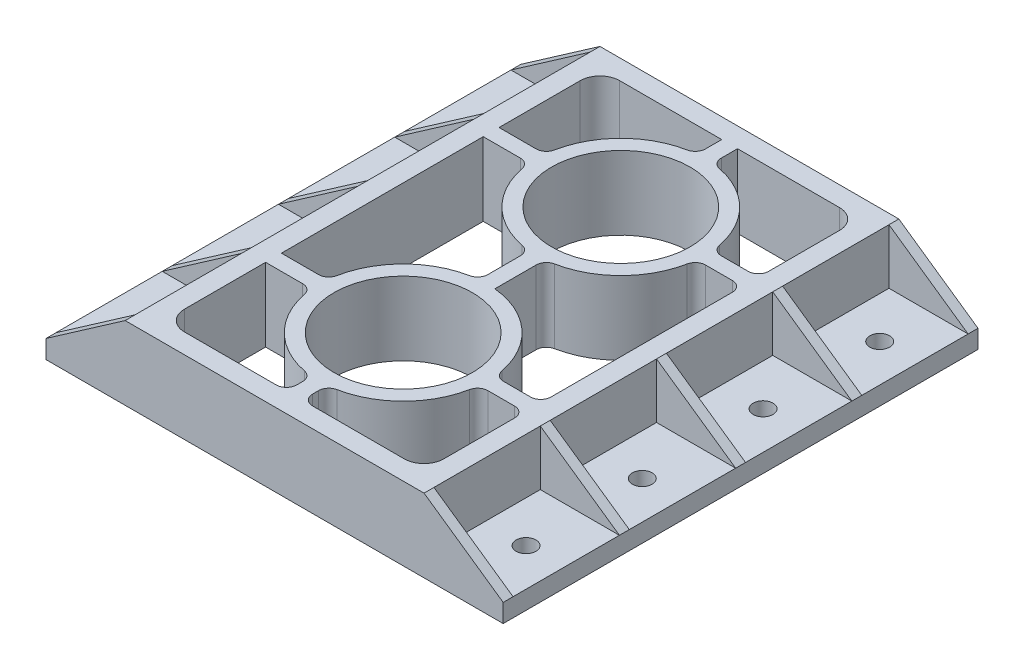
SolidWorks part; units mm, degrees
ref_plane "Front Plane" through (0, 0, 0) normal (0, 0, 1) x (1, 0, 0)
ref_plane "Top Plane" through (0, 0, 0) normal (0, 1, 0) x (1, 0, 0)
ref_plane "Right Plane" through (0, 0, 0) normal (1, 0, 0) x (0, 0, -1)
sketch "Sketch1" plane through (0, 0, 0) normal (0, 0, 1) x (1, 0, 0)
  line L0 (39.1322, 0) -> (112.5008, 0)
  line L1 (112.5008, 0) -> (112.5008, 5.8909)
  line L2 (112.5008, 5.8909) -> (87.1008, 5.8909)
  line L3 (87.1008, 5.8909) -> (87.1008, 23.5635)
  line L4 (87.1008, 23.5635) -> (39.1322, 23.5635)
  line L5 (39.1322, 23.5635) -> (39.1322, 0)
  dimension "D1" = 25.4
extrude "Extrude1" add sketch "Sketch1" against normal blind 152.4
mirror "Mirror1" about plane through (39.1322, 23.5635, -152.4) normal (-1, 0, 0) of "Extrude1"
ref_plane "Plane1" through (39.4584, 56.7117, 0) normal (-0.5711, -0.8209, 0) x (0.8209, -0.5711, 0)
ref_plane "Plane4" through (0, 0, 0) normal (0, 0, 1) x (1, 0, 0)
sketch "Sketch6" plane through (0, 0, 0) normal (0, 0, 1) x (1, 0, 0)
  line L0 (87.1008, 23.5635) -> (112.5008, 5.8909)
  line L1 (112.5008, 5.8909) -> (87.1008, 5.8909)
  line L2 (87.1008, 5.8909) -> (87.1008, 23.5635)
extrude "Extrude2" add sketch "Sketch6" against normal blind 3.175
ref_plane "Plane5" through (0, 0, -152.4) normal (0, 0, -1) x (-1, 0, 0)
ref_plane "Plane6" through (0, 5.8909, 0) normal (0, 1, 0) x (-1, 0, 0)
sketch "Sketch8" plane through (0, 5.8909, 0) normal (0, 1, 0) x (-1, 0, 0)
  circle A0 centre (-100.3959, -19.4469) radius 3.175
  circle A1 centre (-100.3959, -56.7531) radius 3.175
  circle A2 centre (-100.3959, -95.519) radius 3.175
  circle A3 centre (-100.3959, -132.9531) radius 3.175
extrude "Extrude4" cut sketch "Sketch8" against normal through all
pattern_linear "LPattern1" count 5 spacing 37.3062 along (0, 0, -1) of "Extrude2"
ref_plane "Plane8" through (39.1322, 0, 0) normal (1, 0, 0) x (0, 0, -1)
mirror "Mirror5" about plane through (39.1322, 0, 0) normal (1, 0, 0) of "LPattern1", "Extrude4", "Extrude2"
ref_plane "Plane9" through (0, 23.5635, 0) normal (0, 1, 0) x (-1, 0, 0)
sketch "Sketch11" plane through (0, 23.5635, 0) normal (0, 1, 0) x (-1, 0, 0)
  line L51 (-80.7508, -139.7) -> (-80.7508, -12.7)
  line L52 (2.4863, -139.7) -> (2.4863, -12.7)
  line L80 (2.4863, -6.35) -> (-80.7508, -6.35)
  line L81 (-80.7508, -6.35) -> (-80.7508, -37.3062)
  line L82 (-80.7508, -37.3062) -> (-80.7508, -40.4813)
  line L83 (-80.7508, -40.4813) -> (-80.7508, -74.6125)
  line L84 (-80.7508, -74.6125) -> (-80.7508, -77.7875)
  line L85 (-80.7508, -77.7875) -> (-80.7508, -111.9188)
  line L86 (-80.7508, -111.9188) -> (-80.7508, -115.0938)
  line L87 (-80.7508, -115.0938) -> (-80.7508, -146.05)
  line L88 (-80.7508, -146.05) -> (2.4863, -146.05)
  line L89 (2.4863, -146.05) -> (2.4863, -115.0938)
  line L90 (2.4863, -115.0938) -> (2.4863, -111.9188)
  line L91 (2.4863, -111.9188) -> (2.4863, -77.7875)
  line L92 (2.4863, -77.7875) -> (2.4863, -74.6125)
  line L93 (2.4863, -74.6125) -> (2.4863, -40.4813)
  line L94 (2.4863, -40.4813) -> (2.4863, -37.3063)
  line L95 (2.4863, -37.3063) -> (2.4863, -6.35)
  line L96 (-3.8637, -6.35) -> (-74.4008, -6.35)
  line L104 (-74.4008, -146.05) -> (-3.8637, -146.05)
  arc A0 (-74.4008, -6.35) -> (-80.7508, -12.7) centre (-74.4008, -12.7) ccw
  arc A1 (-3.8637, -6.35) -> (2.4863, -12.7) centre (-3.8637, -12.7) cw
  arc A2 (-3.8637, -146.05) -> (2.4863, -139.7) centre (-3.8637, -139.7) ccw
  arc A3 (-80.7508, -139.7) -> (-74.4008, -146.05) centre (-74.4008, -139.7) ccw
  dimension "D2" = 6.35
extrude "Extrude5" cut sketch "Sketch11" against normal blind 25.4
sketch "Sketch12" plane through (0, 23.5635, 0) normal (0, 1, 0) x (-1, 0, 0)
  line L3 (-80.7508, -76.2) -> (2.4863, -76.2) construction
  line L4 (-80.7508, -12.7) -> (-80.7508, -139.7) construction
  line L5 (2.4863, -139.7) -> (2.4863, -12.7) construction
  circle A0 centre (-39.1322, -41.275) radius 22.225
  circle A1 centre (-39.1322, -111.125) radius 22.225
extrude "Extrude-Thin2" add sketch "Sketch12" against normal up to vertex thin
sketch "Sketch13" plane through (0, 23.5635, 0) normal (0, 1, 0) x (-1, 0, 0)
  line L0 (-80.7508, -38.735) -> (-80.7508, -43.815)
  line L1 (-41.6722, -2.8575) -> (-36.5922, -2.8575)
  line L2 (-80.7508, -43.815) -> (-62.9708, -43.815)
  line L3 (-41.6722, -66.3575) -> (-36.5922, -66.3575)
  line L4 (-62.9708, -38.735) -> (-62.9708, -43.815)
  line L5 (-41.6722, -86.6775) -> (-36.5922, -86.6775)
  line L6 (-14.6847, -38.735) -> (-14.6847, -43.815)
  line L7 (4.3653, -38.735) -> (4.3653, -43.815)
  line L8 (-41.6722, -16.8275) -> (-36.5922, -16.8275)
  line L10 (2.9174, -108.585) -> (2.9174, -113.665)
  line L11 (-41.6722, -2.8575) -> (-41.6722, -16.8275)
  line L12 (-41.6722, -66.3575) -> (-41.6722, -86.6775)
  line L13 (-41.6722, -135.9234) -> (-41.6722, -148.6093)
  line L14 (-13.5926, -113.665) -> (2.9174, -113.665)
  line L15 (-80.7508, -113.665) -> (-65.5108, -113.665)
  line L16 (-14.6847, -43.815) -> (4.3653, -43.815)
  line L17 (-36.5922, -2.8575) -> (-36.5922, -16.8275)
  line L18 (-36.5922, -66.3575) -> (-36.5922, -86.6775)
  line L19 (-36.5922, -135.9234) -> (-36.5922, -148.6093)
  line L20 (-13.5926, -108.585) -> (2.9174, -108.585)
  line L21 (-80.7508, -108.585) -> (-65.5108, -108.585)
  line L22 (-14.6847, -38.735) -> (4.3653, -38.735)
  line L23 (-80.7508, -38.735) -> (-62.9708, -38.735)
  line L24 (-13.5926, -108.585) -> (-13.5926, -113.665)
  line L26 (-65.5108, -108.585) -> (-65.5108, -113.665)
  line L27 (-80.7508, -108.585) -> (-80.7508, -113.665)
  line L28 (-41.6722, -148.6093) -> (-36.5922, -148.6093)
  line L30 (-41.6722, -135.9234) -> (-36.5922, -135.9234)
extrude "Extrude6" add sketch "Sketch13" against normal up to vertex (23.5635 mm away)
fillet "Fillet1" radius 3.302 21 edges at (36.5922, 11.7817, -68.1427) (12.2645, 11.7817, -43.815) (41.6722, 11.7817, -6.35) (41.6722, 11.7817, -14.4073) (80.7508, 11.7817, -38.735) (65.9999, 11.7817, -38.735) (80.7508, 11.7817, -43.815) (65.9999, 11.7817, -43.815) (41.6722, 11.7817, -84.2573) (36.5922, 11.7817, -84.2573) (12.2645, 11.7817, -113.665) (12.2645, 11.7817, -108.585) (36.5922, 11.7817, -137.9927) (41.6722, 11.7817, -137.9927) (80.7508, 11.7817, -113.665) (80.7508, 11.7817, -108.585) (65.9999, 11.7817, -108.585) (65.9999, 11.7817, -113.665) (36.5922, 11.7817, -6.35) (36.5922, 11.7817, -14.4073) (12.2645, 11.7817, -38.735)
